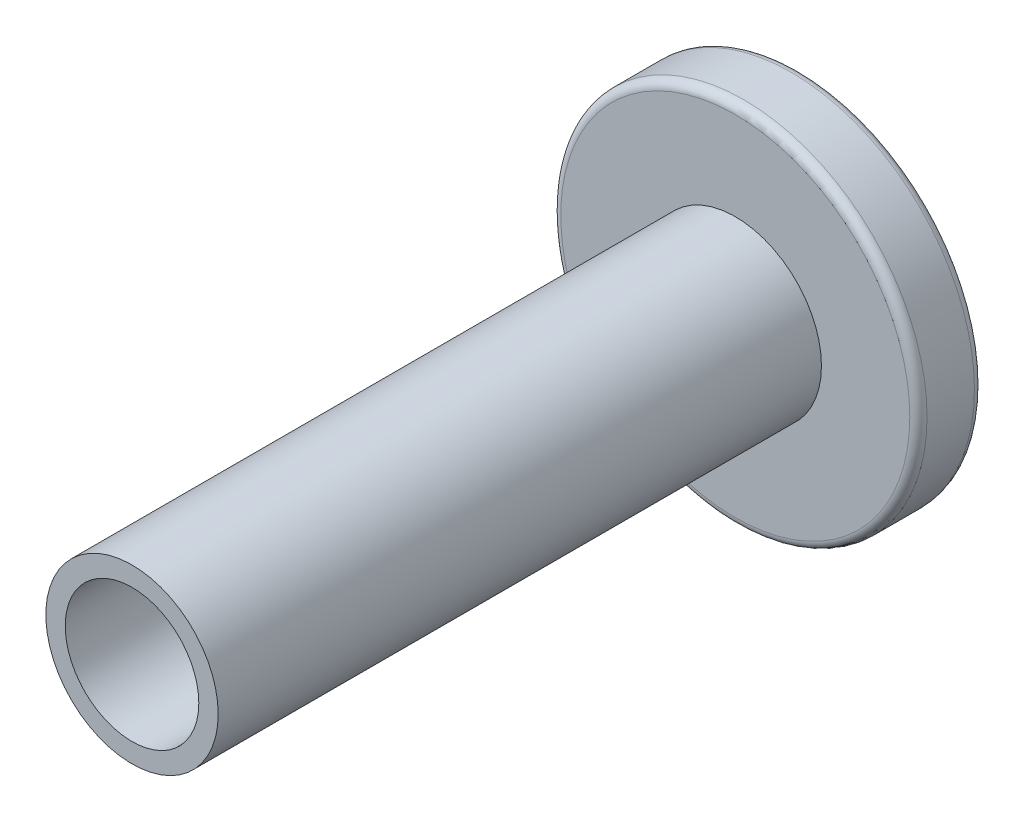
SolidWorks part; units mm, degrees
material "AISI 304"
ref_plane "前视基准面" through (0, 0, 0) normal (0, 0, 1) x (1, 0, 0)
ref_plane "上视基准面" through (0, 0, 0) normal (0, 1, 0) x (1, 0, 0)
ref_plane "右视基准面" through (0, 0, 0) normal (1, 0, 0) x (0, 0, -1)
other "Configuration Table"
sketch "草图1" plane through (0, 0, 0) normal (0, 0, 1) x (1, 0, 0)
  circle A0 centre (0, 0) radius 4.25
  dimension "D1" = 8.5
extrude "凸台-拉伸1" add sketch "草图1" along normal blind 1.5
sketch "草图2" plane through (0, 0, 1.5) normal (0, 0, 1) x (1, 0, 0)
  circle A0 centre (0, 0) radius 2
  circle A1 centre (0, 0) radius 1.55
  dimension "D1" = 4
  dimension "D2" = 3.1
extrude "凸台-拉伸2" add sketch "草图2" along normal blind 14
fillet "圆角1" radius 0.2 2 edges at (4.25, 0, 0) (4.25, 0, 1.5)
sketch "草图3" plane through (0, 0, 0) normal (0, 0, -1) x (-1, 0, 0)
  line L0 (0, 0) -> (1.4434, 0) construction
  line L1 (1.4434, 0) -> (0.7217, 1.25)
  line L2 (0.7217, 1.25) -> (-0.7217, 1.25)
  line L3 (-0.7217, 1.25) -> (-1.4434, 0)
  line L4 (-1.4434, 0) -> (-0.7217, -1.25)
  line L5 (-0.7217, -1.25) -> (0.7217, -1.25)
  line L6 (0.7217, -1.25) -> (1.4434, 0)
  circle A0 centre (0, 0) radius 1.25 construction
  dimension "D1" = 2.5
extrude "切除-拉伸1" cut sketch "草图3" against normal blind 1.5
